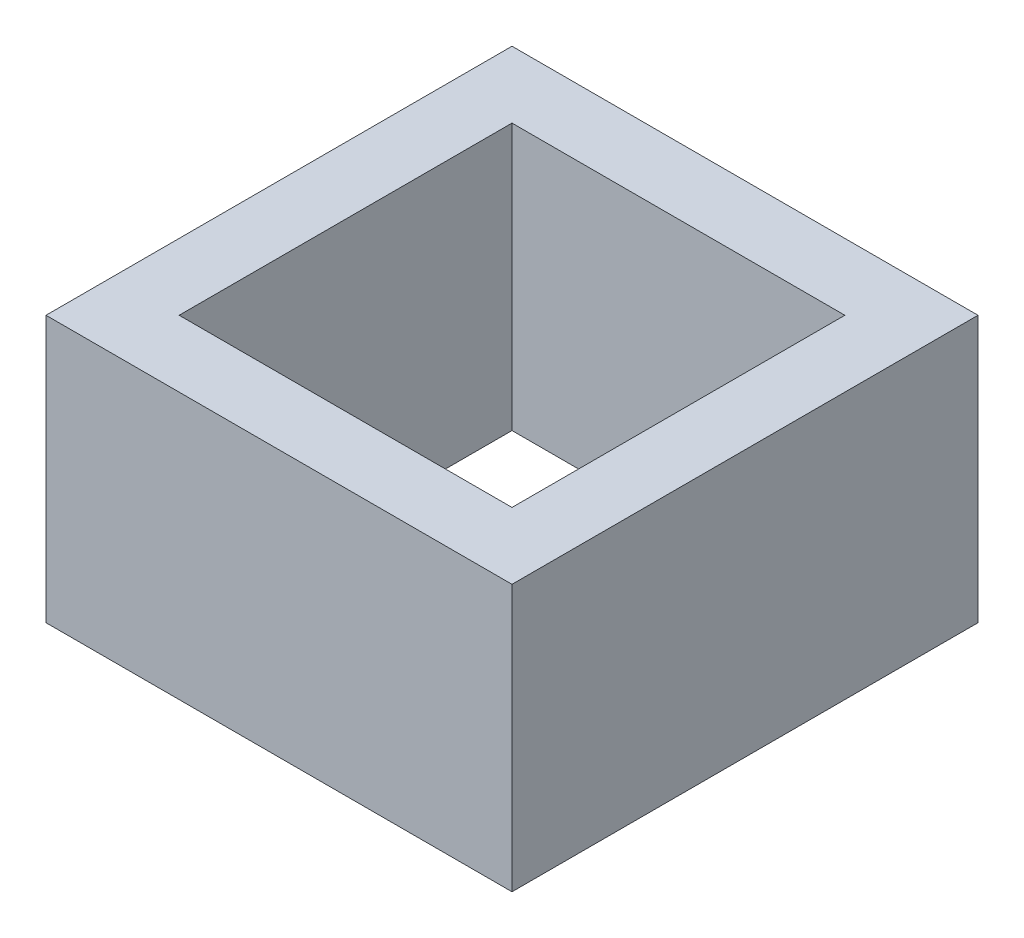
SolidWorks part; units mm, degrees
ref_plane "Front Plane" through (0, 0, 0) normal (0, 0, 1) x (1, 0, 0)
ref_plane "Top Plane" through (0, 0, 0) normal (0, 1, 0) x (1, 0, 0)
ref_plane "Right Plane" through (0, 0, 0) normal (1, 0, 0) x (0, 0, -1)
sketch "Sketch1" plane through (0, 0, 0) normal (0, 1, 0) x (1, 0, 0)
  line L1 (-12.5, 12.5) -> (12.5, 12.5)
  line L2 (-12.5, 12.5) -> (-12.5, -12.5)
  line L3 (-12.5, -12.5) -> (12.5, -12.5)
  line L4 (12.5, 12.5) -> (12.5, -12.5)
  line L5 (-12.5, 12.5) -> (12.5, -12.5) construction
  line L6 (-12.5, -12.5) -> (12.5, 12.5) construction
  line L7 (-17.5, 17.5) -> (17.5, 17.5)
  line L8 (-17.5, 17.5) -> (-17.5, -17.5)
  line L9 (-17.5, -17.5) -> (17.5, -17.5)
  line L10 (17.5, 17.5) -> (17.5, -17.5)
  line L11 (-17.5, 17.5) -> (17.5, -17.5) construction
  line L12 (-17.5, -17.5) -> (17.5, 17.5) construction
  point P0 (0, 0)
  point P6 (0, 0)
  dimension "D1" = 25
  dimension "D2" = 25
  dimension "D3" = 5
  dimension "D4" = 5
extrude "Boss-Extrude1" add sketch "Sketch1" along normal blind 20
